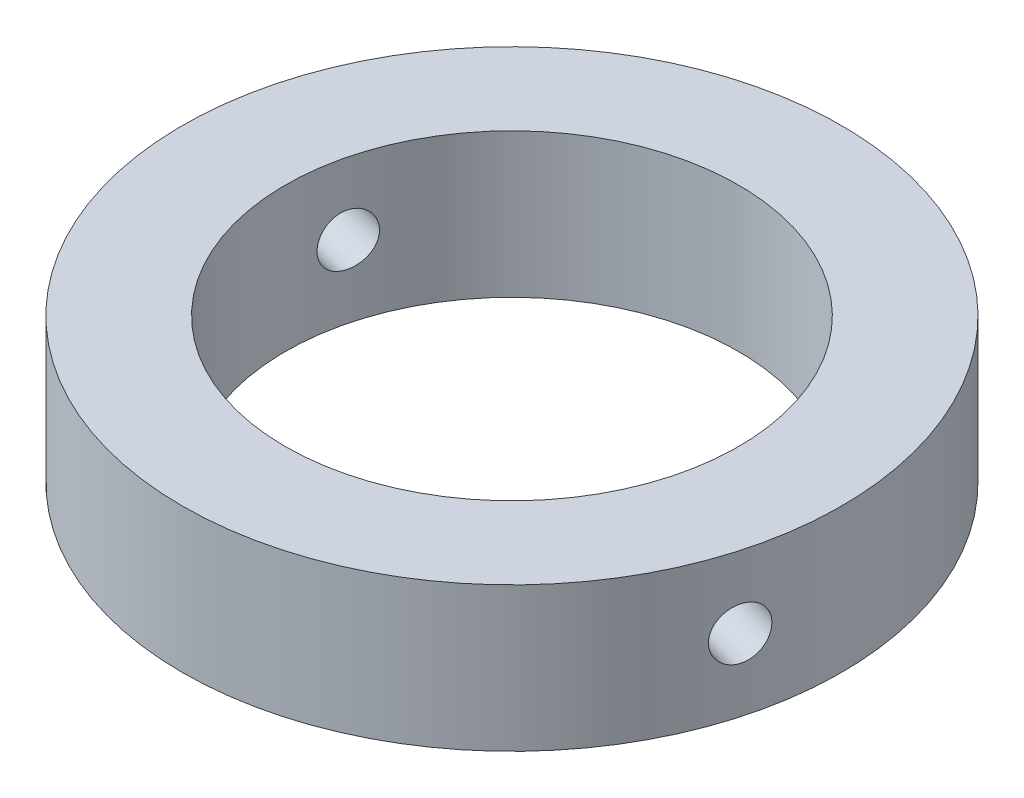
SolidWorks part; units mm, degrees
ref_plane "Front Plane" through (0, 0, 0) normal (0, 0, 1) x (1, 0, 0)
ref_plane "Top Plane" through (0, 0, 0) normal (0, 1, 0) x (1, 0, 0)
ref_plane "Right Plane" through (0, 0, 0) normal (1, 0, 0) x (0, 0, -1)
sketch "Sketch2" plane through (0, 0, 0) normal (0, 1, 0) x (1, 0, 0)
  circle A0 centre (0, 0) radius 11
  circle A1 centre (0, 0) radius 16
  dimension "D1" = 22
  dimension "D2" = 32
extrude "Boss-Extrude1" add sketch "Sketch2" along normal blind 7
hole_wizard "M3x0.5 Tapped Hole1" positions "3DSketch1" profile "Sketch3" tap size "M3x0.5" standard "ANSI Metric"
sketch3d "3DSketch1"
  point P1 (-15.5203, 3.5266, -3.8885)
sketch "Sketch3" plane through (-15.5203, 3.5266, -3.8885) normal (0, 1, 0) x (-0.243, 0, 0.97)
  line L0 (0, 0) -> (0, 5)
  line L1 (0, 5) -> (1.25, 5)
  line L2 (1.25, 5) -> (1.25, 0)
  line L5 (1.25, 0) -> (0, 0)
  line L11 (0, -6.35) -> (0, 107.95) construction
  dimension "Thru Tap Drill Dia." = 2.5
  dimension "Thru Tap Drill Depth" = 5
cosmetic thread "Hole Thread1" parameters "D2"=3
hole_wizard "M3x0.5 Tapped Hole2" positions "3DSketch3" profile "Sketch5" tap size "M3x0.5" standard "ANSI Metric"
sketch3d "3DSketch3"
  point P0 (15.4119, 3.4981, 4.2981)
sketch "Sketch5" plane through (15.4119, 3.4981, 4.2981) normal (0, 1, 0) x (0.2686, 0, -0.9632)
  line L0 (0, 0) -> (0, 4)
  line L1 (0, 4) -> (1.25, 3.2489)
  line L2 (1.25, 3.2489) -> (1.25, 0)
  line L5 (1.25, 0) -> (0, 0)
  line L10 (0, 4) -> (-1.25, 3.2489) construction
  line L11 (0, -6.35) -> (0, 107.95) construction
  dimension "Tap Drill Dia." = 2.5
  dimension "Tap Drill Depth" = 4
  dimension "Drill Angle" = 118
cosmetic thread "Hole Thread2" parameters "D1"=6, "D2"=3
